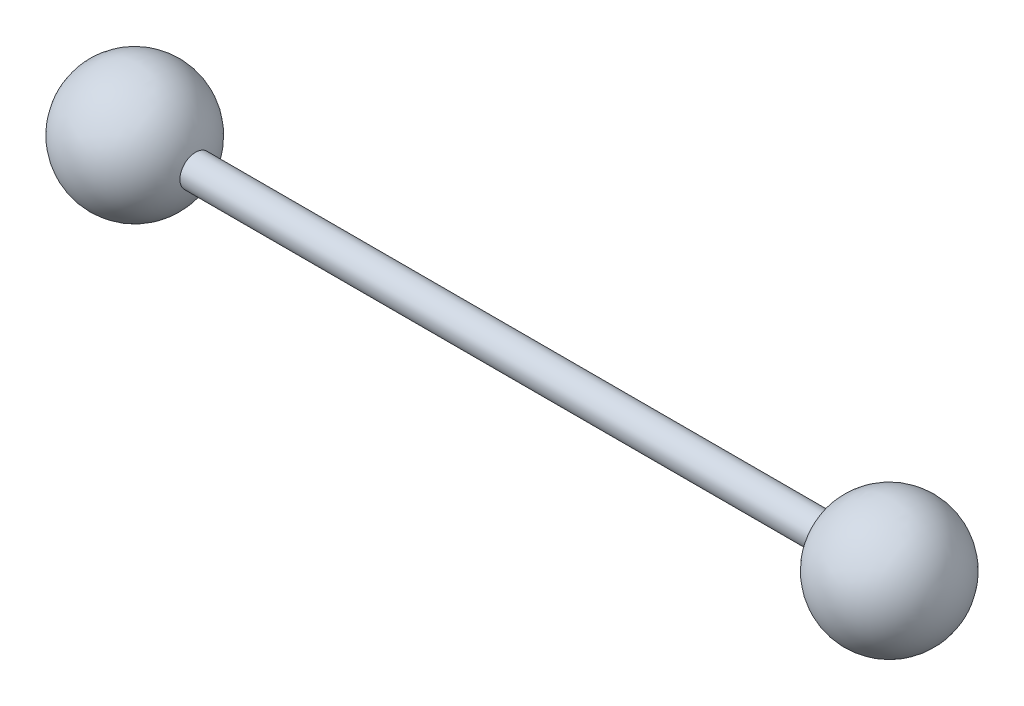
SolidWorks part; units mm, degrees
ref_plane "Plan de face" through (0, 0, 0) normal (0, 0, 1) x (1, 0, 0)
ref_plane "Plan de dessus" through (0, 0, 0) normal (0, 1, 0) x (1, 0, 0)
ref_plane "Plan de droite" through (0, 0, 0) normal (1, 0, 0) x (0, 0, -1)
sketch "Esquisse1" plane through (0, 0, 0) normal (0, 0, 1) x (1, 0, 0)
  line L0 (-9.6383, 0) -> (19.9484, 0) construction
  line L1 (-10, 0) -> (10, 0)
  arc A0 (-10, 0) -> (10, 0) centre (0, 0) cw
  dimension "D1" = 10
revolve "Révolution3" add sketch "Esquisse1" angle 360 about L0
pattern_linear "Répétition linéaire1" count 2 spacing 120 along (1, 0, 0) of bodies 101
sketch "Esquisse2" plane through (0, 0, 0) normal (1, 0, 0) x (0, 0, -1)
  circle A0 centre (0, 0) radius 2.5
  dimension "D1" = 5
extrude "Boss.-Extru.1" add sketch "Esquisse2" along normal up to surface (110.3175 mm away)
